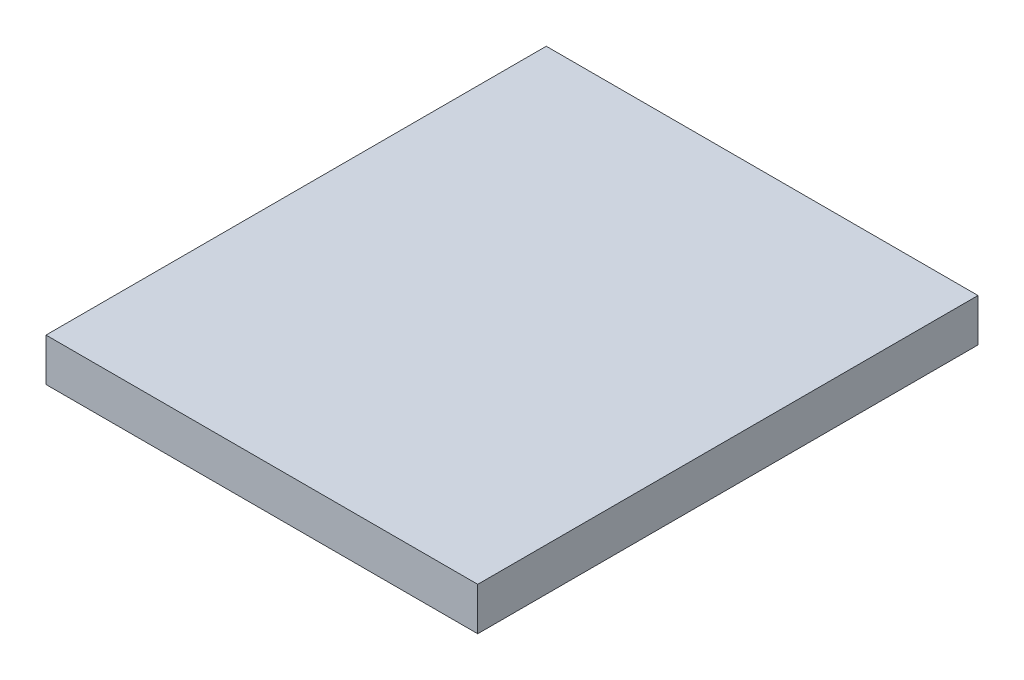
SolidWorks part; units mm, degrees
ref_plane "Front Plane" through (0, 0, 0) normal (0, 0, 1) x (1, 0, 0)
ref_plane "Top Plane" through (0, 0, 0) normal (0, 1, 0) x (1, 0, 0)
ref_plane "Right Plane" through (0, 0, 0) normal (1, 0, 0) x (0, 0, -1)
sketch "Sketch1" plane through (0, 0, 0) normal (0, 1, 0) x (1, 0, 0)
  line L1 (0, 0) -> (63, 0)
  line L2 (0, 0) -> (0, -73)
  line L3 (0, -73) -> (63, -73)
  line L4 (63, 0) -> (63, -73)
  dimension "D1" = 63
  dimension "D2" = 73
extrude "Boss-Extrude1" add sketch "Sketch1" along normal blind 6.25
sketch "Sketch2" plane through (0, 0, 0) normal (0, 0, 1) x (1, 0, 0)
  line L0 (44.5, 3.125) -> (45, 3.125) construction
  line L1 (57, 1.5) -> (55, 1.5)
  line L2 (57, 1.5) -> (57, 4.75)
  line L3 (57, 4.75) -> (55, 4.75)
  line L4 (55, 1.5) -> (55, 4.75)
  line L5 (54.5, 1.5) -> (52.5, 1.5)
  line L6 (54.5, 1.5) -> (54.5, 4.75)
  line L7 (54.5, 4.75) -> (52.5, 4.75)
  line L8 (52.5, 1.5) -> (52.5, 4.75)
  line L9 (52, 1.5) -> (50, 1.5)
  line L10 (52, 1.5) -> (52, 4.75)
  line L11 (52, 4.75) -> (50, 4.75)
  line L12 (50, 1.5) -> (50, 4.75)
  line L13 (49.5, 1.5) -> (47.5, 1.5)
  line L14 (49.5, 1.5) -> (49.5, 4.75)
  line L15 (49.5, 4.75) -> (47.5, 4.75)
  line L16 (47.5, 1.5) -> (47.5, 4.75)
  line L17 (47, 1.5) -> (45, 1.5)
  line L18 (47, 1.5) -> (47, 4.75)
  line L19 (47, 4.75) -> (45, 4.75)
  line L20 (45, 1.5) -> (45, 4.75)
  line L21 (44.5, 1.5) -> (42.5, 1.5)
  line L22 (44.5, 1.5) -> (44.5, 4.75)
  line L23 (44.5, 4.75) -> (42.5, 4.75)
  line L24 (42.5, 1.5) -> (42.5, 4.75)
  line L25 (47, 3.125) -> (47.5, 3.125) construction
  line L26 (49.5, 3.125) -> (50, 3.125) construction
  line L27 (52, 3.125) -> (52.5, 3.125) construction
  line L28 (54.5, 3.125) -> (55, 3.125) construction
  line L29 (63, 6.25) -> (63, 0) construction
  line L30 (63, 6.25) -> (63, 0) construction
  point P36 (63, 3.125)
  point P37 (57, 3.125)
  dimension "D1" = 2
  dimension "D2" = 6
  dimension "D3" = 3.25
  dimension "D4" = 20.5
extrude "Cut-Extrude1" cut sketch "Sketch2" along normal blind 0.1
sketch "Sketch3" plane through (0, 0, 0) normal (0, 0, 1) x (1, 0, 0)
  line L0 (55.7373, 2.3581) -> (55.7373, 2.8581)
  line L1 (55.7373, 2.8581) -> (55.2373, 2.8581)
  line L2 (55.2373, 2.8581) -> (55.2373, 3.3581)
  line L3 (55.2373, 3.3581) -> (55.7373, 3.3581)
  line L4 (55.7373, 3.3581) -> (55.7373, 3.8581)
  line L5 (55.7373, 3.8581) -> (56.2373, 3.8581)
  line L6 (56.2373, 3.8581) -> (56.2373, 3.3581)
  line L7 (56.2373, 3.3581) -> (56.7373, 3.3581)
  line L8 (56.7373, 3.3581) -> (56.7373, 2.8581)
  line L9 (56.7373, 2.8581) -> (56.2373, 2.8581)
  line L10 (56.2373, 2.8581) -> (56.2373, 2.3581)
  line L11 (56.2373, 2.3581) -> (55.7373, 2.3581)
  line L13 (50.2245, 2.8581) -> (51.7245, 2.8581)
  line L14 (50.2245, 2.8581) -> (50.2245, 3.3581)
  line L15 (50.2245, 3.3581) -> (51.7245, 3.3581)
  line L16 (51.7245, 2.8581) -> (51.7245, 3.3581)
  dimension "D1" = 0.5
  dimension "D2" = 1.5
extrude "Cut-Extrude2" cut sketch "Sketch3" along normal blind 0.2
